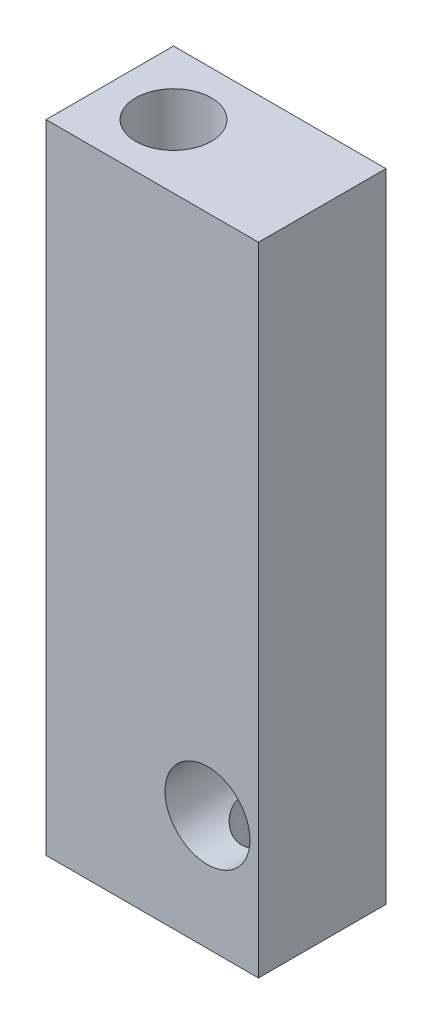
SolidWorks part; units mm, degrees
ref_plane "Front Plane" through (0, 0, 0) normal (0, 0, 1) x (1, 0, 0)
ref_plane "Top Plane" through (0, 0, 0) normal (0, 1, 0) x (1, 0, 0)
ref_plane "Right Plane" through (0, 0, 0) normal (1, 0, 0) x (0, 0, -1)
sketch "Sketch1" plane through (0, 0, 0) normal (0, 1, 0) x (1, 0, 0)
  line L1 (-3.175, -1.905) -> (3.175, -1.905)
  line L2 (-3.175, -1.905) -> (-3.175, 1.905)
  line L3 (-3.175, 1.905) -> (3.175, 1.905)
  line L4 (3.175, -1.905) -> (3.175, 1.905)
  line L5 (-3.175, -1.905) -> (3.175, 1.905) construction
  line L6 (-3.175, 1.905) -> (3.175, -1.905) construction
  point P0 (0, 0)
  dimension "D1" = 3.81
  dimension "D2" = 6.35
extrude "Boss-Extrude1" add sketch "Sketch1" against normal blind 19.05
hole_wizard "#4-40 Tapped Hole1" positions "Sketch3" profile "Sketch2" tap size "#4-40" standard "ANSI Inch"
sketch "Sketch3" plane through (0, 0, 0) normal (0, 1, 0) x (1, 0, 0)
  line L0 (-3.175, 1.905) -> (-3.175, -1.905) construction
  point P0 (-1.27, 0)
  dimension "D1" = 1.905
sketch "Sketch2" plane through (-1.27, 0, 0) normal (1, 0, 0) x (0, 0, 1)
  line L0 (0, 0) -> (0, 8.2992)
  line L1 (0, 8.2992) -> (1.1303, 7.62)
  line L2 (1.1303, 7.62) -> (1.1303, 0)
  line L5 (1.1303, 0) -> (0, 0)
  line L10 (0, 8.2992) -> (-1.1303, 7.62) construction
  line L11 (0, -6.35) -> (0, 107.95) construction
  dimension "Tap Drill Dia." = 2.2606
  dimension "Tap Drill Depth" = 7.62
  dimension "Drill Angle" = 118
cosmetic thread "Hole Thread1" parameters "D1"=5.588, "D2"=2.8448
sketch "Sketch7" plane through (0, 0, 1.905) normal (0, 0, 1) x (1, 0, 0)
  line L0 (3.175, -14.3993) -> (1.4288, -14.3993)
  line L1 (3.175, -19.05) -> (3.175, 0) construction
  line L2 (0.635, -15.193) -> (0.635, -16.0185)
  line L3 (1.4288, -16.8123) -> (3.175, -16.8123)
  line L4 (3.175, -16.8123) -> (3.175, -14.3993)
  line L5 (-3.175, 0) -> (3.175, 0) construction
  arc A0 (1.4288, -16.8123) -> (0.635, -16.0185) centre (1.4288, -16.0185) cw
  arc A1 (0.635, -15.193) -> (1.4288, -14.3993) centre (1.4288, -15.193) cw
  point P14 (0.635, -15.6058)
  dimension "D1" = 0.7937
  dimension "D2" = 15.6058
  dimension "D3" = 2.54
  dimension "D4" = 2.413
extrude "Cut-Extrude2" [suppressed] cut sketch "Sketch7" against normal through all
hole_wizard "#2-56 Tapped Hole1" [suppressed] positions "Sketch6" profile "Sketch5" tap size "#2-56" standard "ANSI Inch"
sketch "Sketch6" [suppressed] plane through (14.0597, -19.05, 1.2056) normal (0, 1, 0) x (0, 0, 1)
  line L13 (0.6994, -12.2182) -> (-3.1106, -12.2182) construction
  line L14 (-3.1106, -10.8847) -> (-3.1106, -17.2347) construction
  line L16 (0.6994, -13.4247) -> (0.6994, -12.6309) construction
  line L17 (0.6994, -13.4247) -> (0.6994, -12.6309)
  line L18 (0.6994, -17.2347) -> (0.6994, -10.8847) construction
  point P0 (-1.2056, -12.2182)
  dimension "D1" = 1.2065
cosmetic thread "Hole Thread2" parameters "D1"=2.3965, "D2"=2.1844
sketch "Sketch5" plane through (1.8415, -19.05, 0) normal (1, 0, 0) x (0, 0, -1)
  line L0 (0, 0) -> (0, 3.5657)
  line L1 (0, 3.5657) -> (0.889, 3.0315)
  line L2 (0.889, 3.0315) -> (0.889, 0)
  line L5 (0.889, 0) -> (0, 0)
  line L10 (0, 3.5657) -> (-0.889, 3.0315) construction
  line L11 (0, -6.35) -> (0, 107.95) construction
  dimension "Tap Drill Dia." = 1.778
  dimension "Tap Drill Depth" = 3.0315
  dimension "Drill Angle" = 118
sketch "Sketch8" plane through (0, 0, 1.905) normal (0, 0, 1) x (1, 0, 0)
  line L0 (-3.175, 0) -> (3.175, 0) construction
  line L1 (3.175, -19.05) -> (3.175, 0) construction
  circle A0 centre (1.651, -15.6058) radius 1.27
  dimension "D3" = 2.54
  dimension "D1" = 15.6058
  dimension "D2" = 1.524
extrude "Cut-Extrude3" cut sketch "Sketch8" against normal through all
hole_wizard "#2-56 Tapped Hole2" positions "Sketch11" profile "Sketch10" tap size "#2-56" standard "ANSI Inch"
sketch "Sketch11" plane through (0, -19.05, 0) normal (0, -1, 0) x (-1, 0, 0)
  line L0 (-2.921, -1.905) -> (-0.381, -1.905) construction
  line L1 (-2.921, -1.905) -> (-0.381, -1.905) construction
  line L2 (-1.651, -1.905) -> (-1.651, 1.905) construction
  line L3 (-3.175, 1.905) -> (3.175, 1.905) construction
  point P0 (-1.651, 0)
sketch "Sketch10" plane through (1.651, -19.05, 0) normal (1, 0, 0) x (0, 0, -1)
  line L0 (0, 0) -> (0, 2.1742)
  line L1 (0, 2.1742) -> (0.889, 2.1742)
  line L2 (0.889, 2.1742) -> (0.889, 0)
  line L5 (0.889, 0) -> (0, 0)
  line L11 (0, -6.35) -> (0, 107.95) construction
  dimension "Thru Tap Drill Dia." = 1.778
  dimension "Thru Tap Drill Depth" = 2.1742
cosmetic thread "Hole Thread3" parameters "D2"=2.1844
chamfer "Chamfer1" [suppressed] distance 2.54 angle 45
chamfer "Chamfer2" [suppressed] distance 2.54 angle 45
